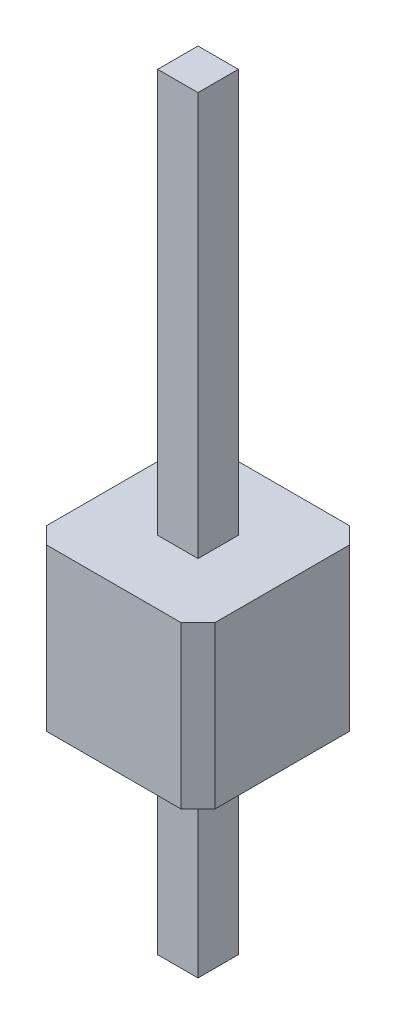
SolidWorks part; units mm, degrees
ref_plane "Alzado" through (0, 0, 0) normal (0, 0, 1) x (1, 0, 0)
ref_plane "Planta" through (0, 0, 0) normal (0, 1, 0) x (1, 0, 0)
ref_plane "Vista lateral" through (0, 0, 0) normal (1, 0, 0) x (0, 0, -1)
sketch "Croquis1" plane through (0, 0, 0) normal (0, 1, 0) x (1, 0, 0)
  line L0 (-1.25, 1.25) -> (-1, 1.25) construction
  line L1 (-1, 1.25) -> (1, 1.25)
  line L2 (-1.25, 1) -> (-1.25, -1)
  line L3 (-1, -1.25) -> (1, -1.25)
  line L4 (1.25, 1) -> (1.25, -1)
  line L5 (-1.25, 1.25) -> (1.25, -1.25) construction
  line L6 (-1.25, -1.25) -> (1.25, 1.25) construction
  line L7 (-1, 1.25) -> (-1.25, 1) construction
  line L8 (-1.25, 1) -> (-1.25, 1.25) construction
  line L9 (-1, 1.25) -> (-1.25, 1)
  line L10 (1.25, 1.25) -> (1, 1.25) construction
  line L11 (1, 1.25) -> (1.25, 1) construction
  line L12 (1.25, 1) -> (1.25, 1.25) construction
  line L13 (1.25, -1.25) -> (1.25, -1) construction
  line L14 (1.25, -1) -> (1, -1.25) construction
  line L15 (1, -1.25) -> (1.25, -1.25) construction
  line L16 (-1.25, -1.25) -> (-1.25, -1) construction
  line L17 (-1.25, -1) -> (-1, -1.25) construction
  line L18 (-1, -1.25) -> (-1.25, -1.25) construction
  line L19 (1, 1.25) -> (1.25, 1)
  line L20 (1.25, -1) -> (1, -1.25)
  line L21 (-1.25, -1) -> (-1, -1.25)
  point P0 (0, 0)
  dimension "D1" = 2.5
  dimension "D2" = 2.5
  dimension "D3" = 0.25
  dimension "D4" = 0.25
  dimension "D5" = 0.25
  dimension "D6" = 0.25
  dimension "D7" = 0.25
  dimension "D8" = 0.25
extrude "Saliente-Extruir1" add sketch "Croquis1" along normal blind 2.4
sketch "Croquis2" plane through (0, 2.4, 0) normal (0, 1, 0) x (1, 0, 0)
  line L1 (-0.3, 0.3) -> (0.3, 0.3)
  line L2 (-0.3, 0.3) -> (-0.3, -0.3)
  line L3 (-0.3, -0.3) -> (0.3, -0.3)
  line L4 (0.3, 0.3) -> (0.3, -0.3)
  line L5 (-0.3, 0.3) -> (0.3, -0.3) construction
  line L6 (-0.3, -0.3) -> (0.3, 0.3) construction
  point P0 (0, 0)
  dimension "D1" = 0.6
  dimension "D2" = 0.6
extrude "Saliente-Extruir2" add sketch "Croquis2" along normal blind 6
sketch "Croquis3" plane through (0, 0, 0) normal (0, -1, 0) x (1, 0, 0)
  line L1 (-0.3, 0.3) -> (0.3, 0.3)
  line L2 (-0.3, 0.3) -> (-0.3, -0.3)
  line L3 (-0.3, -0.3) -> (0.3, -0.3)
  line L4 (0.3, 0.3) -> (0.3, -0.3)
  line L5 (-0.3, 0.3) -> (0.3, -0.3) construction
  line L6 (-0.3, -0.3) -> (0.3, 0.3) construction
  point P0 (0, 0)
  dimension "D1" = 0.6
  dimension "D2" = 0.6
extrude "Saliente-Extruir3" add sketch "Croquis3" along normal blind 3 and the other way blind 2
